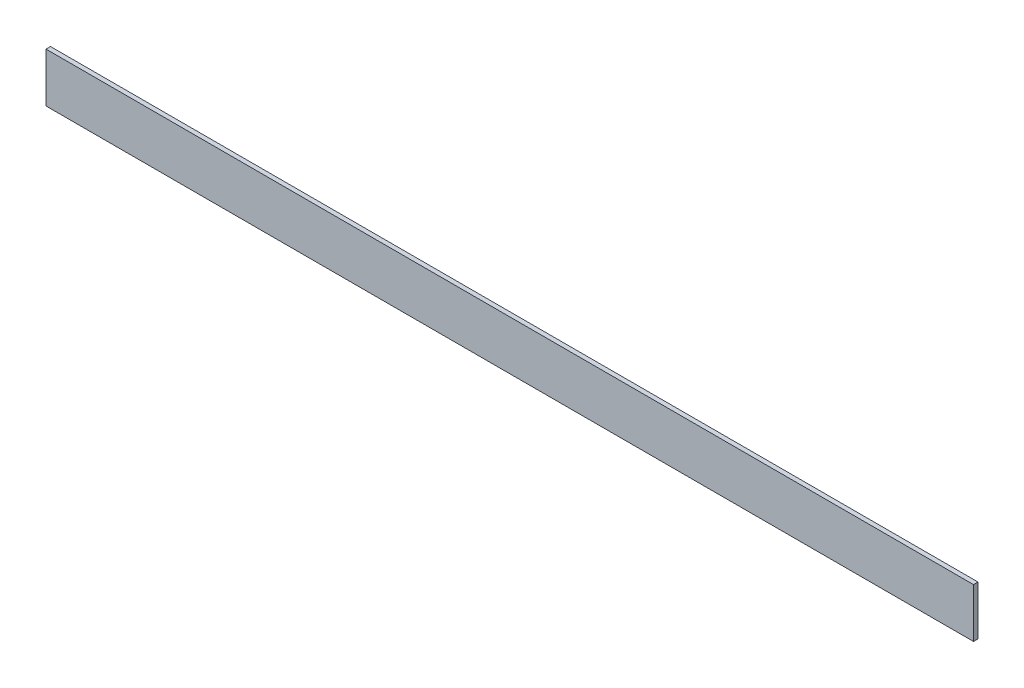
SolidWorks part; units mm, degrees
ref_plane "Front Plane" through (0, 0, 0) normal (0, 0, 1) x (1, 0, 0)
ref_plane "Top Plane" through (0, 0, 0) normal (0, 1, 0) x (1, 0, 0)
ref_plane "Right Plane" through (0, 0, 0) normal (1, 0, 0) x (0, 0, -1)
sketch "Top return above tread profile" plane through (0, 0, 0) normal (0, 0, 1) x (1, 0, 0)
  line L0 (-117, -5.5) -> (90, -5.5)
  line L1 (90, -5.5) -> (90, 5.5)
  line L2 (90, 5.5) -> (-117, 5.5)
  line L3 (-117, 5.5) -> (-117, -5.5)
extrude "Top return above tread" add sketch "Top return above tread profile" along normal blind 1
